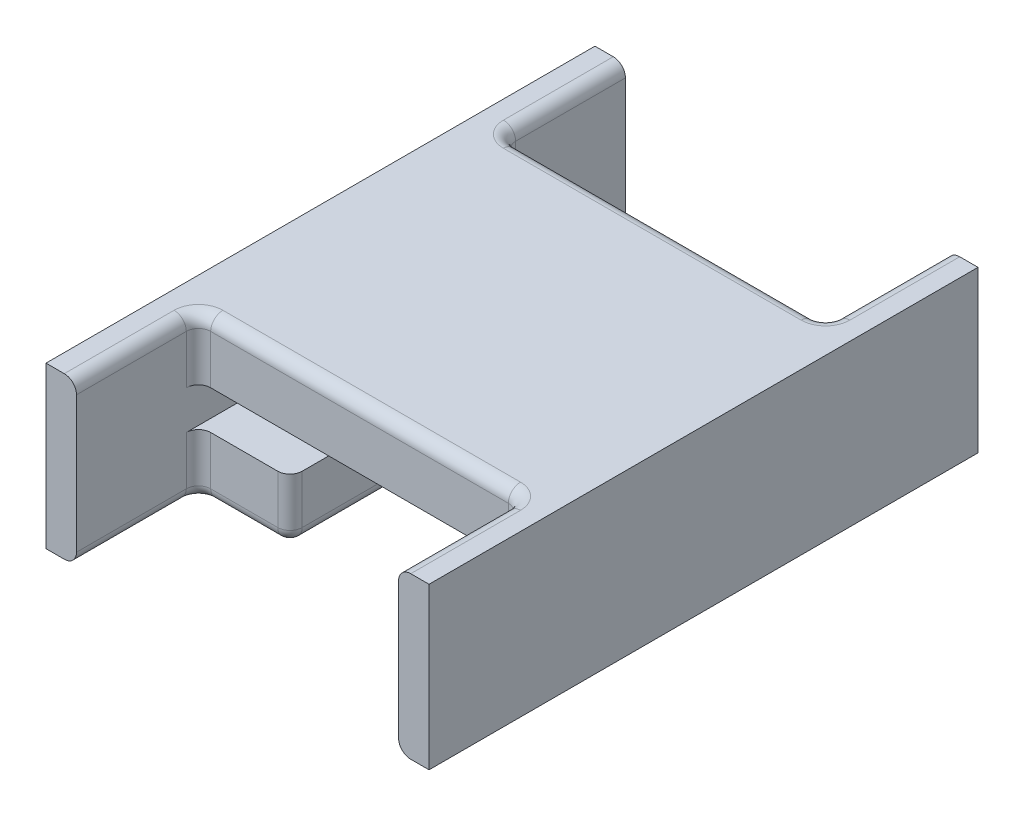
SolidWorks part; units mm, degrees
ref_plane "Front Plane" through (0, 0, 0) normal (0, 0, 1) x (1, 0, 0)
ref_plane "Top Plane" through (0, 0, 0) normal (0, 1, 0) x (1, 0, 0)
ref_plane "Right Plane" through (0, 0, 0) normal (1, 0, 0) x (0, 0, -1)
sketch "Sketch1" plane through (0, 0, 0) normal (0, 0, 1) x (1, 0, 0)
  line L0 (27.2929, 8.5491) -> (-35.5071, 8.5491)
  line L1 (-35.5071, 8.5491) -> (-35.5071, -17.8009)
  line L2 (-35.5071, -17.8009) -> (-15.5071, -17.8009)
  line L3 (-15.5071, -17.8009) -> (-15.5071, -7.8009)
  line L4 (-15.5071, -7.8009) -> (-30.5071, -7.8009)
  line L5 (-30.5071, -7.8009) -> (-30.5071, -1.4509)
  line L6 (-30.5071, -1.4509) -> (22.2929, -1.4509)
  line L7 (-4.1071, 8.5491) -> (-4.1071, -1.4509) construction
  line L8 (22.2929, -7.8009) -> (22.2929, -1.4509)
  line L9 (7.2929, -7.8009) -> (22.2929, -7.8009)
  line L10 (7.2929, -17.8009) -> (7.2929, -7.8009)
  line L11 (27.2929, -17.8009) -> (7.2929, -17.8009)
  line L12 (27.2929, 8.5491) -> (27.2929, -17.8009)
  dimension "D1" = 26.4
  dimension "D2" = 5
  dimension "D3" = 10
  dimension "D4" = 6.35
  dimension "D5" = 10
  dimension "D6" = 15
extrude "Boss-Extrude1" add sketch "Sketch1" against normal blind 50
ref_plane "Plane 1" through (0, 0, 0) normal (0, 0, 1) x (1, 0, 0)
sketch "Sketch2" plane through (0, 0, 0) normal (0, 0, 1) x (1, 0, 0)
  line L0 (-4.1071, 8.5491) -> (-4.1071, -1.4509) construction
  line L1 (-30.5071, -7.8009) -> (-30.5071, -1.4509) construction
  line L2 (-35.5071, 8.5491) -> (-30.5071, 8.5491)
  line L3 (-35.5071, 8.5491) -> (-35.5071, -17.8009)
  line L4 (-35.5071, -17.8009) -> (-30.5071, -17.8009)
  line L5 (-30.5071, 8.5491) -> (-30.5071, -17.8009)
  line L6 (-35.5071, 8.5491) -> (-35.5071, -17.8009) construction
  line L7 (27.2929, -17.8009) -> (22.2929, -17.8009)
  line L8 (22.2929, 8.5491) -> (22.2929, -17.8009)
  line L9 (27.2929, 8.5491) -> (22.2929, 8.5491)
  line L10 (27.2929, 8.5491) -> (27.2929, -17.8009)
  dimension "D1" = 0
  dimension "D2" = 0
extrude "Boss-Extrude2" add sketch "Sketch2" along normal blind 20 contours L3 L4 L5 L2 | L8 L7 L10 L9
ref_plane "Plane2" through (0, 0, -50) normal (0, 0, -1) x (-1, 0, 0)
sketch "Sketch4" plane through (0, 0, -50) normal (0, 0, -1) x (-1, 0, 0)
  line L0 (4.1071, 8.5491) -> (4.1071, -1.4509) construction
  line L1 (-27.2929, 8.5491) -> (-22.2929, 8.5491)
  line L2 (-27.2929, 8.5491) -> (-27.2929, -17.8009)
  line L3 (-27.2929, -17.8009) -> (-22.2929, -17.8009)
  line L4 (-22.2929, 8.5491) -> (-22.2929, -17.8009)
  line L5 (-22.2929, -1.4509) -> (-22.2929, -7.8009) construction
  line L6 (-27.2929, -17.8009) -> (-27.2929, 8.5491) construction
  line L7 (35.5071, -17.8009) -> (30.5071, -17.8009)
  line L8 (30.5071, 8.5491) -> (30.5071, -17.8009)
  line L9 (35.5071, 8.5491) -> (30.5071, 8.5491)
  line L10 (35.5071, 8.5491) -> (35.5071, -17.8009)
  dimension "D1" = 0
  dimension "D2" = 0
extrude "Boss-Extrude3" add sketch "Sketch4" along normal blind 20
fillet "Fillet2" radius 2 28 edges at (-30.5071, -12.8009, -50) (-30.5071, 3.5491, -50) (-30.5071, -17.8009, -60) (-30.5071, 8.5491, -60) (22.2929, -12.8009, -50) (22.2929, 8.5491, -60) (22.2929, -17.8009, -60) (22.2929, 8.5491, 10) (22.2929, -17.8009, 10) (22.2929, -12.8009, 0) (22.2929, 3.5491, 0) (-30.5071, 3.5491, 0) (-30.5071, 8.5491, 10) (-30.5071, -17.8009, 10) (-23.0071, -17.8009, 0) (-15.5071, -12.8009, 0) (7.2929, -12.8009, 0) (14.7929, -17.8009, 0) (-4.1071, 8.5491, 0) (-23.0071, -17.8009, -50) (-15.5071, -12.8009, -50) (7.2929, -12.8009, -50) (14.7929, -17.8009, -50) (-4.1071, 8.5491, -50) (-15.5071, -17.8009, -25) (7.2929, -17.8009, -25) (-30.5071, -12.8009, 0) (22.2929, 3.5491, -50)
